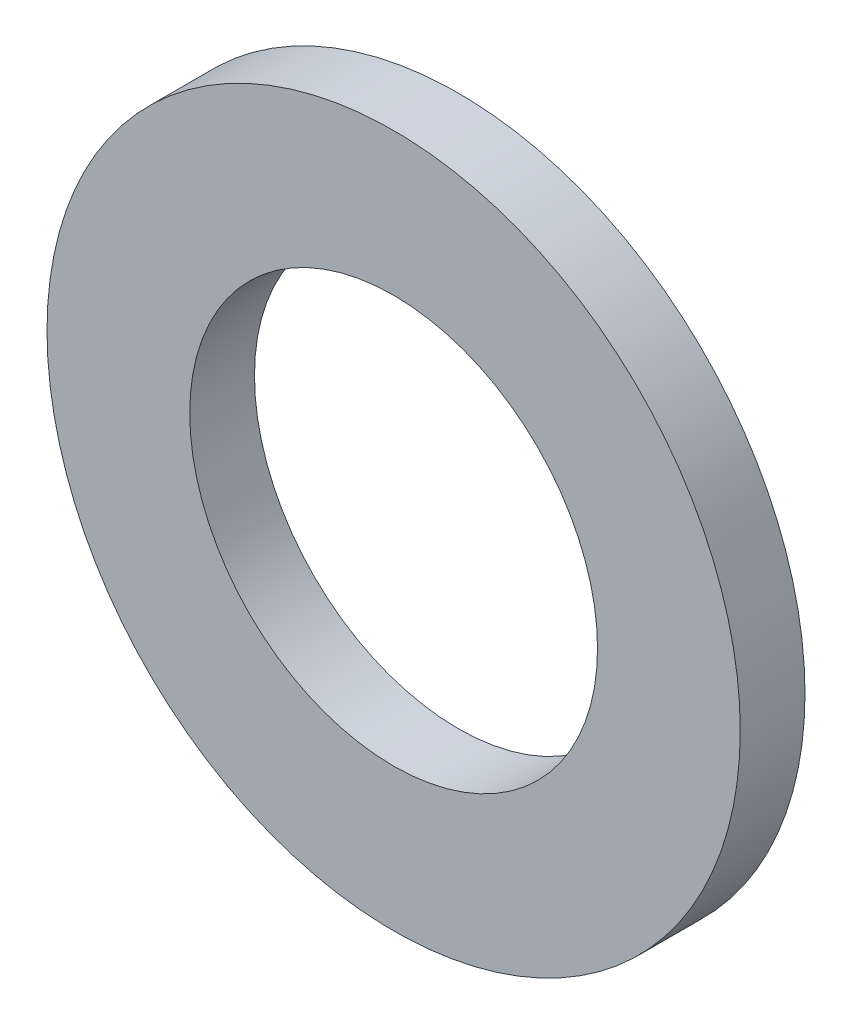
SolidWorks part; units mm, degrees
ref_plane "Front Plane" through (0, 0, 0) normal (0, 0, 1) x (1, 0, 0)
ref_plane "Top Plane" through (0, 0, 0) normal (0, 1, 0) x (1, 0, 0)
ref_plane "Right Plane" through (0, 0, 0) normal (1, 0, 0) x (0, 0, -1)
sketch "Sketch1" plane through (0, 0, 0) normal (0, 0, 1) x (1, 0, 0)
  circle A0 centre (0, 0) radius 8.5
  circle A1 centre (0, 0) radius 5
  dimension "D1" = 17
  dimension "D2" = 10
extrude "Boss-Extrude1" add sketch "Sketch1" along normal blind 1.5875
